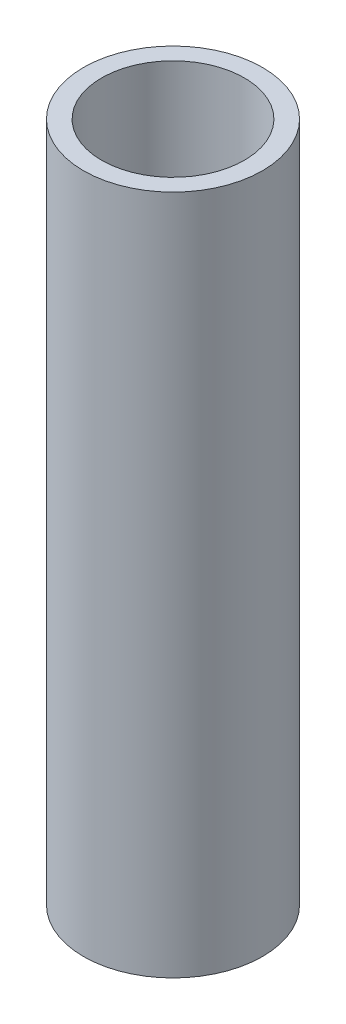
SolidWorks part; units mm, degrees
ref_plane "Front Plane" through (0, 0, 0) normal (0, 0, 1) x (1, 0, 0)
ref_plane "Top Plane" through (0, 0, 0) normal (0, 1, 0) x (1, 0, 0)
ref_plane "Right Plane" through (0, 0, 0) normal (1, 0, 0) x (0, 0, -1)
sketch "Sketch1" plane through (0, 0, 0) normal (0, 1, 0) x (1, 0, 0)
  circle A0 centre (0, 0) radius 13.3223
  circle A1 centre (0, 0) radius 16.7005
  dimension "D1" = 26.6446
  dimension "D2" = 33.401
extrude "Boss-Extrude1" add sketch "Sketch1" along normal blind 127
